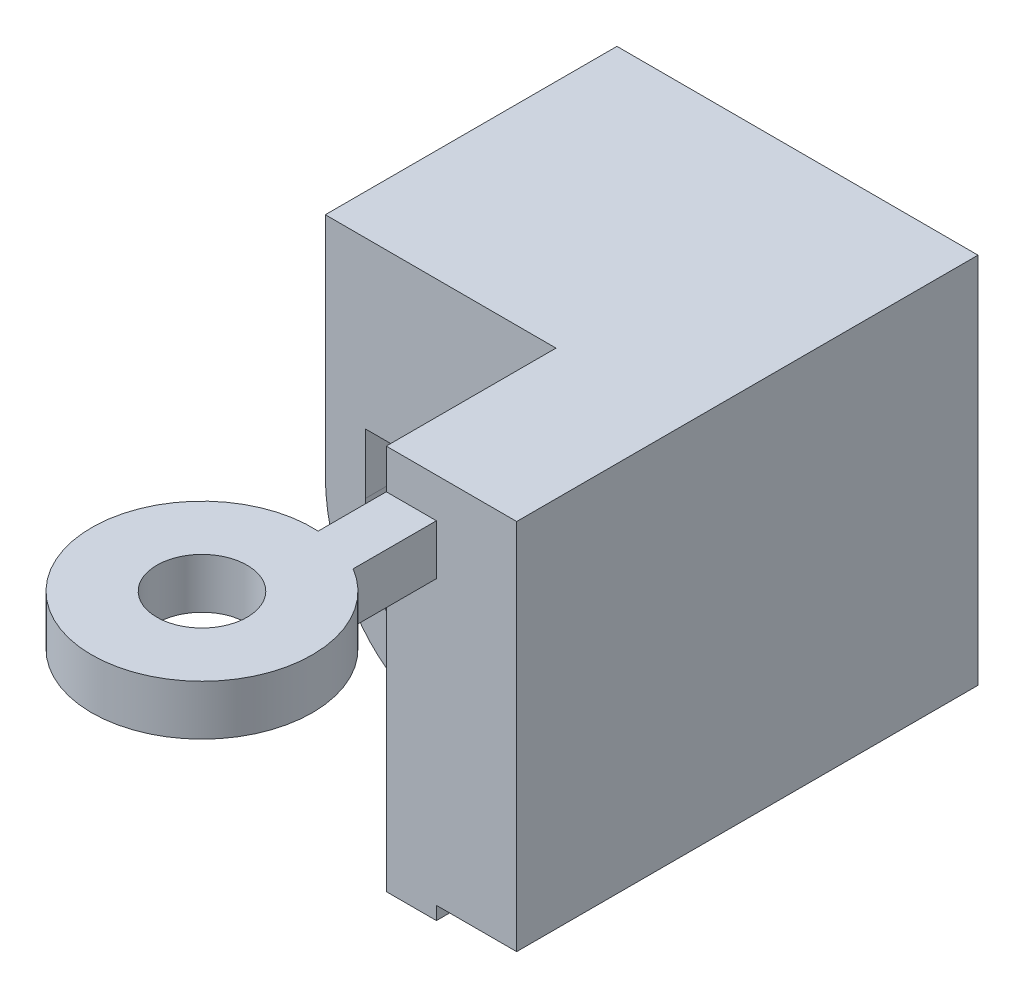
SolidWorks part; units mm, degrees
ref_plane "Front Plane" through (0, 0, 0) normal (0, 0, 1) x (1, 0, 0)
ref_plane "Top Plane" through (0, 0, 0) normal (0, 1, 0) x (1, 0, 0)
ref_plane "Right Plane" through (0, 0, 0) normal (1, 0, 0) x (0, 0, -1)
sketch "Sketch1" plane through (0, 0, 0) normal (0, 0, 1) x (1, 0, 0)
  line L0 (-22.7185, 23.9661) -> (13.2815, 23.9348)
  line L1 (13.2815, 23.9348) -> (13.2815, -13.2108)
  line L2 (-22.7185, 23.9661) -> (-22.7185, 1.4689)
  line L3 (-9.7185, -14.5292) -> (5.2815, -14.5292)
  line L4 (5.2815, -14.5292) -> (5.2815, -13.2108)
  line L5 (5.2815, -13.2108) -> (13.2815, -13.2108)
  line L6 (-18.7185, 7.4681) -> (0.2815, 7.4681)
  line L7 (0.2815, 7.4681) -> (0.2815, -11.5296)
  line L8 (0.2815, -11.5296) -> (-9.7185, -11.5296)
  line L9 (-18.7185, 7.4681) -> (-18.7185, 1.4689)
  arc A0 (-22.7185, 1.4689) -> (-19.057, -9.763) centre (-3.6605, 1.4689) ccw
  arc A1 (-19.057, -9.763) -> (-9.7185, -14.5292) centre (-9.3786, -2.3316) ccw
  arc A2 (-18.7185, 1.4689) -> (-16.1684, -8.0368) centre (-2.2275, 0.798) ccw
  arc A3 (-16.1684, -8.0368) -> (-9.7185, -11.5296) centre (-9.8186, -4.0127) ccw
extrude "Boss-Extrude1" add sketch "Sketch1" along normal blind 46
sketch "Sketch3" plane through (0, -14.5292, 0) normal (0, -1, 0) x (1, 0, 0)
  line L2 (-22.703, 22.0788) -> (0.297, 7.0788) construction
  line L9 (-22.703, 7.0788) -> (0.297, 22.0788) construction
  line L18 (-9.703, 0.0788) -> (-9.703, 7.0788) construction
  line L19 (13.297, 7.9272) -> (-2.703, 7.9272) construction
  line L20 (0.297, 7.0788) -> (0.297, 22.0788)
  line L21 (-22.703, 22.0788) -> (0.297, 22.0788)
  line L22 (-22.703, 7.0788) -> (-22.703, 22.0788)
  line L23 (-22.703, 7.0788) -> (0.297, 7.0788)
  point P26 (-11.203, 14.5788)
extrude "Cut-Extrude2" cut sketch "Sketch3" against normal blind 28
sketch "Sketch10" plane through (0, 7.4681, 0) normal (0, -1, 0) x (-1, 0, 0)
  line L0 (9.7185, -22.0788) -> (9.7185, -29.0788) construction
  line L1 (9.7185, -46) -> (9.7185, -22.0788) construction
  line L2 (-13.2815, -33.0314) -> (-0.2815, -33.0314) construction
  line L3 (-13.2815, -46) -> (-13.2815, 0) construction
  line L5 (-0.2815, -29.0788) -> (22.7185, -29.0788)
  line L6 (-0.2815, -29.0788) -> (-0.2815, -46)
  line L7 (-0.2815, -46) -> (22.7185, -46)
  line L8 (22.7185, -29.0788) -> (22.7185, -46)
  line L9 (-0.2815, -29.0788) -> (22.7185, -46) construction
  line L10 (-0.2815, -46) -> (22.7185, -29.0788) construction
  point P13 (11.2185, -37.5394)
extrude "Cut-Extrude6" cut sketch "Sketch10" along normal blind 40 and the other way blind 30
ref_plane "Plane1" through (0, 20, 0) normal (0, 1, 0) x (1, 0, 0)
sketch "Sketch7" plane through (0, 20, 0) normal (0, 1, 0) x (1, 0, 0)
  line L0 (0.2815, -46) -> (0.2815, -52.7902) construction
  circle A2 centre (-0.3214, -63.7736) radius 11
  circle A3 centre (-0.3214, -63.7736) radius 4.5
  point P2 (0, 0)
extrude "Boss-Extrude2" add sketch "Sketch7" against normal blind 5 separate body
sketch "Sketch12" plane through (0, 20, 0) normal (0, 1, 0) x (1, 0, 0)
  line L0 (0.2815, -46) -> (0.2815, -52.7902)
  line L1 (5.2815, -46) -> (5.2815, -54.3076)
  line L2 (0.2815, -46) -> (5.2815, -46)
  circle A0 centre (-0.3214, -63.7736) radius 11 construction
  arc A1 (0.2815, -52.7902) -> (5.2815, -54.3076) centre (-0.3214, -63.7736) cw
extrude "Boss-Extrude3" add sketch "Sketch12" against normal blind 5
